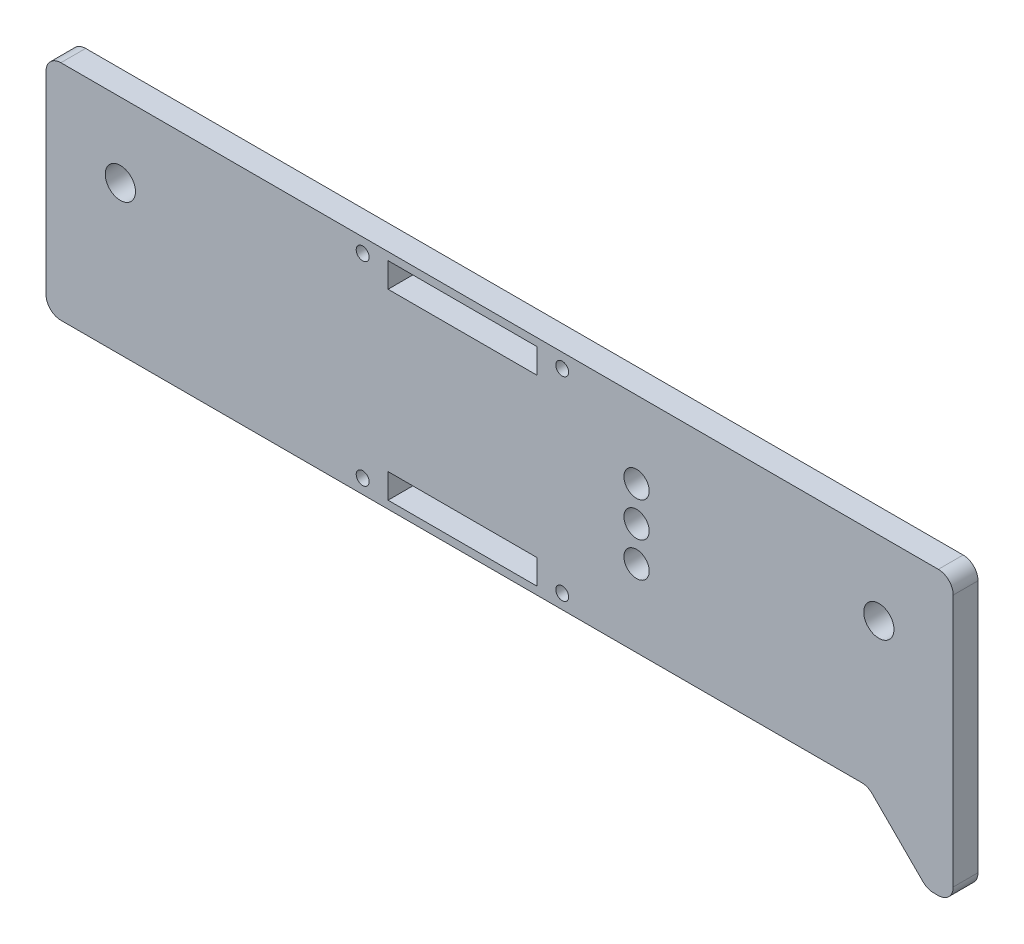
SolidWorks part; units mm, degrees
ref_plane "Front Plane" through (0, 0, 0) normal (0, 0, 1) x (1, 0, 0)
ref_plane "Top Plane" through (0, 0, 0) normal (0, 1, 0) x (1, 0, 0)
ref_plane "Right Plane" through (0, 0, 0) normal (1, 0, 0) x (0, 0, -1)
sketch "Sketch1" plane through (0, 0, 0) normal (0, 0, 1) x (1, 0, 0)
  line L2 (183, -12) -> (183, 45)
  line L3 (183, 45) -> (0, 45)
  line L4 (0, 45) -> (0, 0)
  line L6 (165.78, 0) -> (177.78, -12)
  line L7 (177.78, -12) -> (183, -12)
  line L11 (0, 0) -> (165.78, 0)
  line L12 (63.875, 42.125) -> (63.875, 45) construction
  line L13 (63.875, 2.875) -> (63.875, 0) construction
  line L14 (63.875, 42.125) -> (63.875, 2.875) construction
  line L15 (0, 22.5) -> (63.875, 22.5) construction
  line L16 (119.125, 22.5) -> (183, 22.5) construction
  line L17 (63.875, 43.425) -> (69, 43.425) construction
  line L18 (69, 43.425) -> (99, 43.425)
  line L19 (69, 43.425) -> (69, 38.425)
  line L20 (69, 38.425) -> (99, 38.425)
  line L21 (99, 43.425) -> (99, 38.425)
  line L22 (99, 43.425) -> (104.125, 43.425) construction
  line L23 (69, 6.575) -> (99, 6.575)
  line L24 (99, 1.575) -> (99, 6.575)
  line L25 (69, 1.575) -> (99, 1.575)
  line L26 (69, 1.575) -> (69, 6.575)
  circle A0 centre (15, 30) radius 3.05
  circle A1 centre (168, 30) radius 3.05
  circle A2 centre (119.125, 29.5) radius 2.55
  circle A3 centre (119.125, 22.5) radius 2.55
  circle A4 centre (119.125, 15.5) radius 2.55
  circle A5 centre (63.875, 42.125) radius 1.3
  circle A6 centre (104.125, 42.125) radius 1.3
  circle A7 centre (104.125, 2.875) radius 1.3
  circle A8 centre (63.875, 2.875) radius 1.3
  dimension "D7" = 6.1
  dimension "D8" = 6.1
  dimension "D12" = 5.1
  dimension "D14" = 22.5
  dimension "D4" = 2.6
  dimension "D16" = 15
  dimension "D1" = 183
  dimension "D2" = 57
  dimension "D3" = 45
  dimension "D5" = 2
  dimension "D6" = 5.22
  dimension "D9" = 15
  dimension "D10" = 15
  dimension "D11" = 15
  dimension "D17" = 30
  dimension "D18" = 5
  dimension "D13" = 3
  dimension "D15" = 2
extrude "Boss-Extrude1" add sketch "Sketch1" along normal blind 5
fillet "Fillet1" radius 3 6 edges at (183, 45, 2.5) (183, -12, 2.5) (177.78, -12, 2.5) (165.78, 0, 2.5) (0, 0, 2.5) (0, 45, 2.5)
